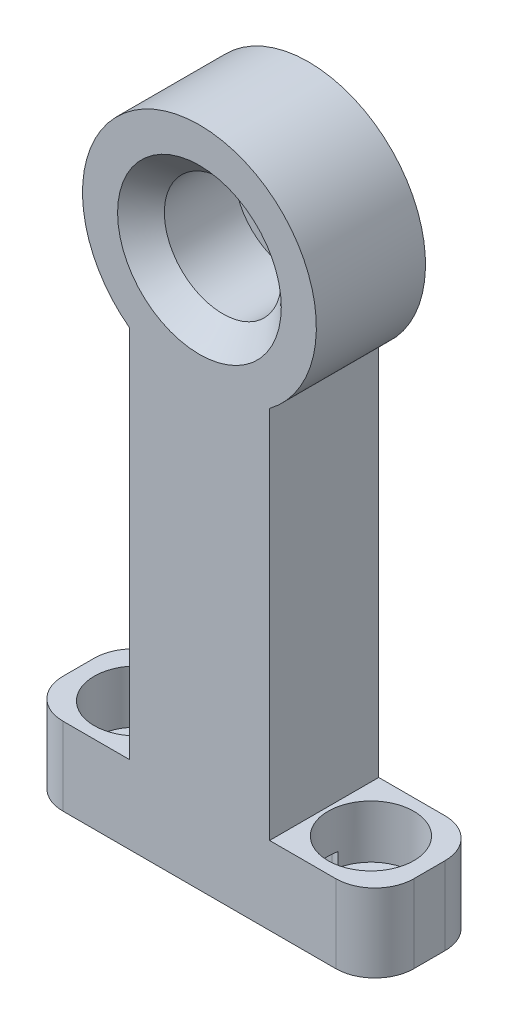
SolidWorks part; units mm, degrees
ref_plane "前视基准面" through (0, 0, 0) normal (0, 0, 1) x (1, 0, 0)
ref_plane "上视基准面" through (0, 0, 0) normal (0, 1, 0) x (1, 0, 0)
ref_plane "右视基准面" through (0, 0, 0) normal (1, 0, 0) x (0, 0, -1)
sketch "草图1" plane through (0, 0, 0) normal (0, 0, 1) x (1, 0, 0)
  circle A0 centre (0, 0) radius 0.5
  circle A1 centre (0, 0) radius 15
  dimension "D1" = 1
  dimension "D2" = 30
extrude "凸台-拉伸1" add sketch "草图1" along normal mid plane 14
sketch "草图2" plane through (0, 0, 7) normal (0, 0, 1) x (1, 0, 0)
  circle A0 centre (0, 0) radius 7.5
  circle A1 centre (0, 0) radius 0.5
  dimension "D1" = 15
extrude "切除-拉伸1" cut sketch "草图2" against normal blind 12
chamfer "倒角1" distance 3 angle 45 1 edges at (7.5, 0, 7)
sketch "草图3" plane through (0, 0, 0) normal (0, 0, 1) x (1, 0, 0)
  line L0 (0, -12) -> (0, -42.8915) construction
  line L2 (-9, -70) -> (9, -70)
  line L3 (-9, -70) -> (-9, -12)
  line L4 (-9, -12) -> (9, -12) construction
  line L5 (9, -70) -> (9, -12)
  line L6 (-9, -70) -> (9, -12) construction
  line L7 (-9, -12) -> (9, -70) construction
  line L8 (22.5, -60) -> (-22.5, -60)
  line L9 (22.5, -60) -> (22.5, -70)
  line L10 (22.5, -70) -> (-22.5, -70)
  line L11 (-22.5, -60) -> (-22.5, -70)
  line L12 (22.5, -60) -> (-22.5, -70) construction
  line L13 (22.5, -70) -> (-22.5, -60) construction
  circle A4 centre (0, 0) radius 15 construction
  circle A5 centre (0, 0) radius 15
  arc A6 (-9, -12) -> (9, -12) centre (0, 0) ccw
  point P0 (0, -41)
  point P4 (0, -65)
  dimension "D2" = 45
  dimension "D3" = 10
  dimension "D4" = 70
  dimension "D1" = 18
  dimension "D5" = 0
extrude "凸台-拉伸2" add sketch "草图3" along normal mid plane 14
sketch "草图4" plane through (0, -70, 0) normal (0, -1, 0) x (1, 0, 0)
  line L0 (-22.5, 0) -> (22.5, 0) construction
  line L1 (-22.5, 7) -> (-22.5, -7) construction
  line L2 (22.5, 7) -> (22.5, -7) construction
  line L3 (0, 0) -> (0, 9.104) construction
  line L4 (6, 0) -> (8, 0) construction
  line L5 (6, 2) -> (8, 2)
  line L6 (6, -2) -> (8, -2)
  arc A1 (6, 2) -> (6, -2) centre (6, 0) ccw
  arc A2 (8, -2) -> (8, 2) centre (8, 0) ccw
  point P13 (7, 0)
  dimension "D1" = 7
  dimension "D2" = 4
  dimension "D3" = 2
extrude "切除-拉伸2" cut sketch "草图4" against normal blind 5
hole_wizard "Ø6.6 (6.6) 直径孔1" [suppressed] positions "草图5" profile "草图6" hole size "Ø6.6" standard "DIN"
sketch "草图5" plane through (0, -60, 0) normal (0, 1, 0) x (1, 0, 0)
  line L1 (0, 0) -> (0, 14.0268) construction
  line L3 (-9, 7) -> (-20, 7) construction
  point P0 (-14.5, 0)
  point P8 (14.5, 0)
  dimension "D1" = 29
  dimension "D2" = 7
sketch "草图6" plane through (-14.5, -60, 0) normal (1, 0, 0) x (0, 0, 1)
  line L0 (0, 0) -> (0, 10)
  line L1 (0, 10) -> (3.3, 10)
  line L2 (3.3, 10) -> (3.3, 0)
  line L5 (3.3, 0) -> (0, 0)
  line L11 (0, -6.35) -> (0, 107.95) construction
  dimension "通孔孔直径" = 6.6
  dimension "通孔孔深度" = 10
fillet "圆角1" radius 5 4 edges at (22.5, -65, -7) (22.5, -65, 7) (-22.5, -65, -7) (-22.5, -65, 7)
sketch "草图7" plane through (0, 0, -7) normal (0, 0, -1) x (-1, 0, 0)
  circle A0 centre (0, 0) radius 2
  circle A1 centre (0, 0) radius 3
  circle A2 centre (0, 0) radius 0.5 construction
  dimension "D2" = 1.5
  dimension "D1" = 1
sketch "草图8" plane through (0, -70, 0) normal (0, -1, 0) x (1, 0, 0)
  line L0 (7, 2) -> (7, 0) construction
  line L1 (8, 2) -> (6, 2) construction
  line L2 (15, 0) -> (-15, 0) construction
  line L3 (7, 0) -> (0, 0) construction
  line L4 (0, 0) -> (-7, 0) construction
  dimension "D1" = 7
hole_wizard "大小mm 暗销孔1" positions "3D草图1" profile "草图9" hole size "Ø4.0" standard "GB"
sketch3d "3D草图1"
  point P0 (-7, -70, 0)
sketch "草图9" plane through (-7, -70, 0) normal (1, 0, 0) x (0, 0, -1)
  line L0 (0, 0) -> (0, 6.2017)
  line L1 (0, 6.2017) -> (2, 5)
  line L2 (2, 5) -> (2, 0)
  line L5 (2, 0) -> (0, 0)
  line L10 (0, 6.2017) -> (-2, 5) construction
  line L11 (0, -6.35) -> (0, 107.95) construction
  dimension "孔直径" = 4
  dimension "孔深度" = 5
  dimension "导头角度" = 118
sketch "草图10" plane through (0, -60, 0) normal (0, 1, 0) x (1, 0, 0)
  line L0 (-15, 0) -> (15, 0) construction
  point P4 (0, 0)
hole_wizard "打孔尺寸(%根据)内六角圆柱头螺钉的类型1" positions "3D草图2" profile "草图11" counterbore size "M6" standard "GB"
sketch3d "3D草图2"
  point P0 (-15, -60, 0)
  point P3 (15, -60, 0)
sketch "草图11" plane through (-15, -60, 0) normal (1, 0, 0) x (0, 0, 1)
  line L0 (0, 0) -> (0, 10)
  line L1 (0, 10) -> (3.2, 10)
  line L3 (3.2, 10) -> (3.2, 6.8)
  line L4 (3.2, 6.8) -> (5.5, 6.8)
  line L5 (5.5, 6.8) -> (5.5, 0)
  line L7 (5.5, 0) -> (0, 0)
  line L11 (0, -6.35) -> (0, 107.95) construction
  dimension "通孔孔直径" = 6.4
  dimension "通孔孔深度" = 10
  dimension "柱形沉头孔直径" = 11
  dimension "柱形沉头孔深度" = 6.8
ref_plane "基准面1" through (0, 0, 0) normal (0, 0, 1) x (1, 0, 0)
